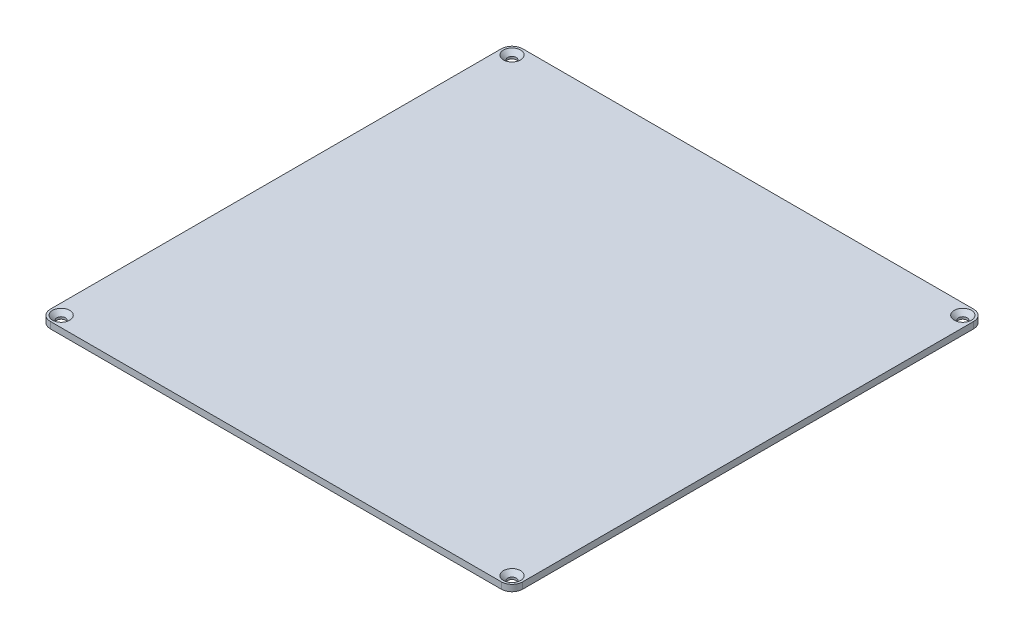
SolidWorks part; units mm, degrees
ref_plane "Front Plane" through (0, 0, 0) normal (0, 0, 1) x (1, 0, 0)
ref_plane "Top Plane" through (0, 0, 0) normal (0, 1, 0) x (1, 0, 0)
ref_plane "Right Plane" through (0, 0, 0) normal (1, 0, 0) x (0, 0, -1)
sketch "Sketch1" plane through (0, 0, 0) normal (0, 1, 0) x (1, 0, 0)
  line L1 (0, 0) -> (-220, 0)
  line L2 (0, 0) -> (0, 220)
  line L3 (0, 220) -> (-220, 220)
  line L4 (-220, 0) -> (-220, 220)
  dimension "D1" = 220
  dimension "D2" = 220
extrude "Boss-Extrude1" add sketch "Sketch1" along normal blind 3
fillet "Fillet1" radius 5 4 edges at (0, 1.5, -220) (0, 1.5, 0) (-220, 1.5, 0) (-220, 1.5, -220)
sketch "Sketch2" plane through (0, 3, 0) normal (0, 1, 0) x (1, 0, 0)
  line L0 (-110, 220) -> (-110, 0) construction
  line L1 (-5, 220) -> (-215, 220) construction
  line L2 (-215, 0) -> (-5, 0) construction
  line L3 (-220, 215) -> (-220, 5) construction
  circle A0 centre (-215, 215) radius 2
  circle A1 centre (-215, 5) radius 2
  circle A2 centre (-5, 5) radius 2
  circle A3 centre (-5, 215) radius 2
  dimension "D1" = 4
  dimension "D2" = 4
  dimension "D3" = 5
  dimension "D4" = 5
extrude "Cut-Extrude1" cut sketch "Sketch2" against normal blind 3
chamfer "Chamfer1" distance 2 angle 45 4 edges at (-215, 3, -3) (-5, 3, -7) (-5, 3, -217) (-215, 3, -213)
